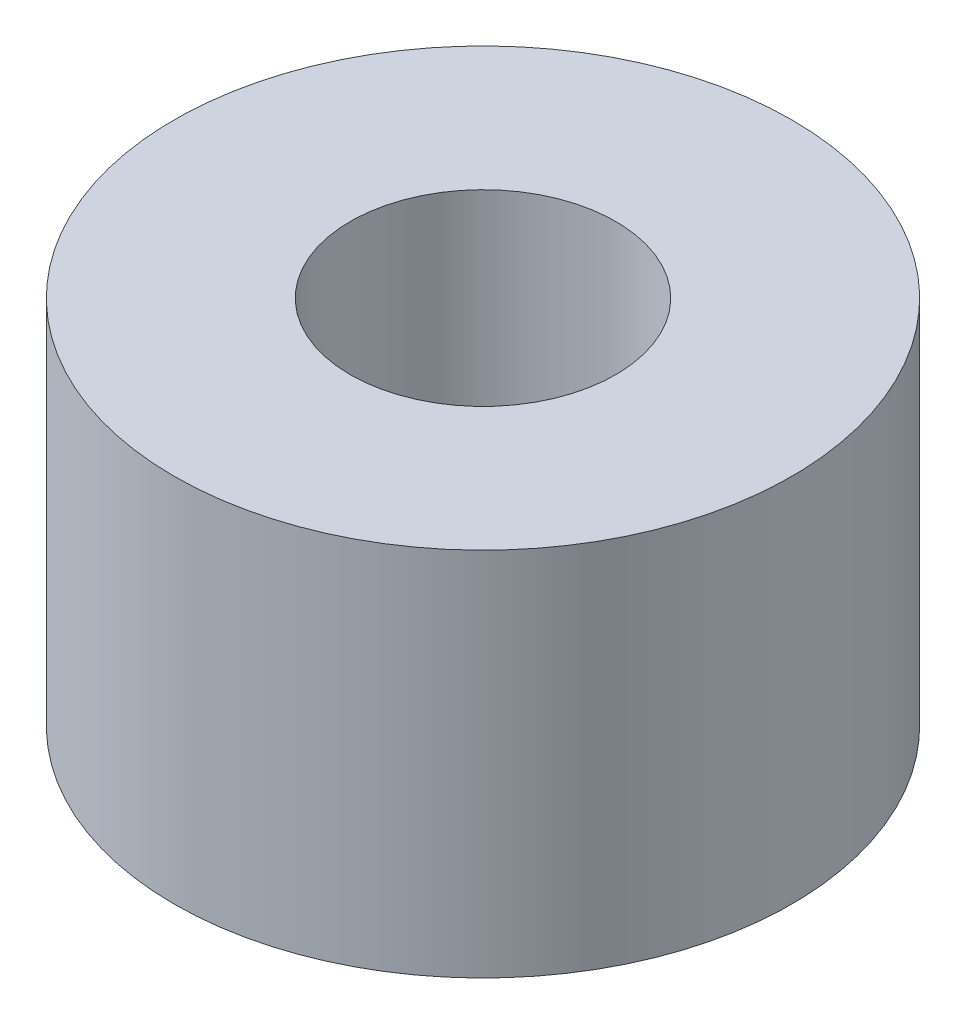
SolidWorks part; units mm, degrees
ref_plane "前视基准面" through (0, 0, 0) normal (0, 0, 1) x (1, 0, 0)
ref_plane "上视基准面" through (0, 0, 0) normal (0, 1, 0) x (1, 0, 0)
ref_plane "右视基准面" through (0, 0, 0) normal (1, 0, 0) x (0, 0, -1)
other "Configuration Table"
sketch "草图1" plane through (0, 0, 0) normal (0, 0, 1) x (1, 0, 0)
  line L0 (0, 0) -> (10, 0)
  line L1 (10, 0) -> (10, 12)
  line L2 (10, 12) -> (0, 12)
  line L3 (0, 12) -> (0, 0)
  line L4 (0, 0) -> (0, 12) construction
  dimension "radius" = 10
  dimension "height" = 12
revolve "Round_pushrod_head" add sketch "草图1" angle 360 about L4
sketch "草图2" plane through (0, 12, 0) normal (0, 1, 0) x (1, 0, 0)
  circle A0 centre (0, 0) radius 4.3
  dimension "diameter" = 8.6
extrude "Axial_bore" cut sketch "草图2" against normal through all
